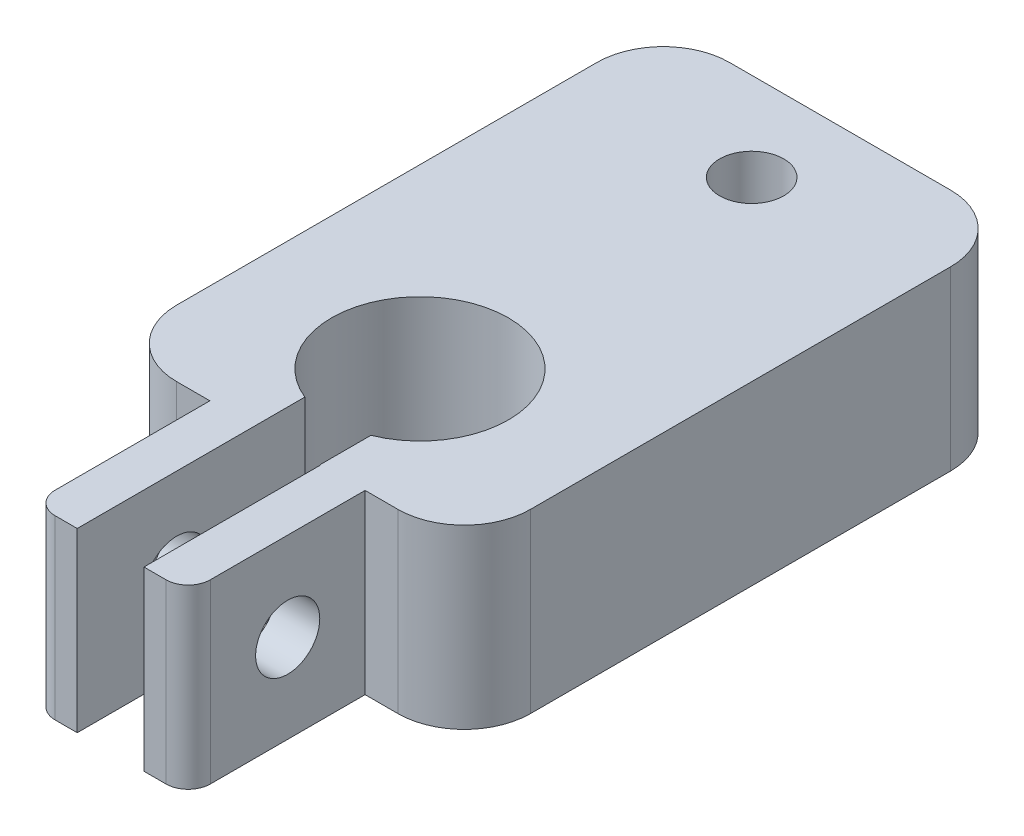
SolidWorks part; units mm, degrees
material "ABS"
ref_plane "Front Plane" through (0, 0, 0) normal (0, 0, 1) x (1, 0, 0)
ref_plane "Top Plane" through (0, 0, 0) normal (0, 1, 0) x (1, 0, 0)
ref_plane "Right Plane" through (0, 0, 0) normal (1, 0, 0) x (0, 0, -1)
sketch "Sketch1" plane through (0, 0, 0) normal (0, 1, 0) x (1, 0, 0)
  line L5 (0, 0) -> (16, 0)
  line L6 (0, 0) -> (0, 25)
  line L7 (0, 25) -> (16, 25)
  line L8 (16, 0) -> (16, 25)
  circle A0 centre (8, 21) radius 1.45
  circle A1 centre (8, 6) radius 4
  dimension "D3" = 2.9
  dimension "D6" = 8
  dimension "D1" = 25
  dimension "D2" = 16
  dimension "D4" = 8
  dimension "D5" = 4
  dimension "D7" = 8
  dimension "D8" = 6
extrude "Boss-Extrude1" add sketch "Sketch1" along normal blind 8
fillet "Fillet1" radius 3 4 edges at (16, 4, -25) (0, 4, -25) (16, 4, 0) (0, 4, 0)
sketch "Sketch2" plane through (0, 8, 0) normal (0, 1, 0) x (1, 0, 0)
  line L1 (3, 0) -> (13, 0) construction
  line L2 (6.5, 0) -> (4.5, 0)
  line L3 (6.5, 0) -> (6.5, -8)
  line L4 (6.5, -8) -> (4.5, -8)
  line L5 (4.5, 0) -> (4.5, -8)
  line L11 (9.5183, 0) -> (11.5183, 0)
  line L12 (9.5183, 0) -> (9.5183, -8)
  line L13 (9.5183, -8) -> (11.5183, -8)
  line L14 (11.5183, 0) -> (11.5183, -8)
  point P10 (8, 0)
  dimension "D1" = 1.5
  dimension "D2" = 2
  dimension "D3" = 8
  dimension "D5" = 2
extrude "Boss-Extrude2" add sketch "Sketch2" against normal through all
fillet "Fillet2" radius 1 1 edges at (4.5, 4, 8)
fillet "Fillet3" radius 1 1 edges at (11.5183, 4, 8)
sketch "Sketch3" plane through (0, 8, 0) normal (0, 1, 0) x (1, 0, 0)
  line L0 (6.5, 2.2919) -> (6.5, -1.7613)
  line L1 (6.5, -1.7613) -> (9.4936, -1.7613)
  line L2 (9.4936, -1.7613) -> (9.4936, 2.2893)
  arc A0 (6.5, 2.2919) -> (9.4936, 2.2893) centre (8, 6) ccw
extrude "Cut-Extrude1" cut sketch "Sketch3" against normal through all
sketch "Sketch5" plane through (11.5183, 0, 0) normal (1, 0, 0) x (0, 0, -1)
  line L0 (-7, 8) -> (-7, 0) construction
  line L1 (-7, 0) -> (0, 0) construction
  circle A0 centre (-3.5, 4) radius 1.45
  dimension "D1" = 2.9
  dimension "D2" = 3.5
  dimension "D3" = 4
extrude "Cut-Extrude3" cut sketch "Sketch5" against normal through all
